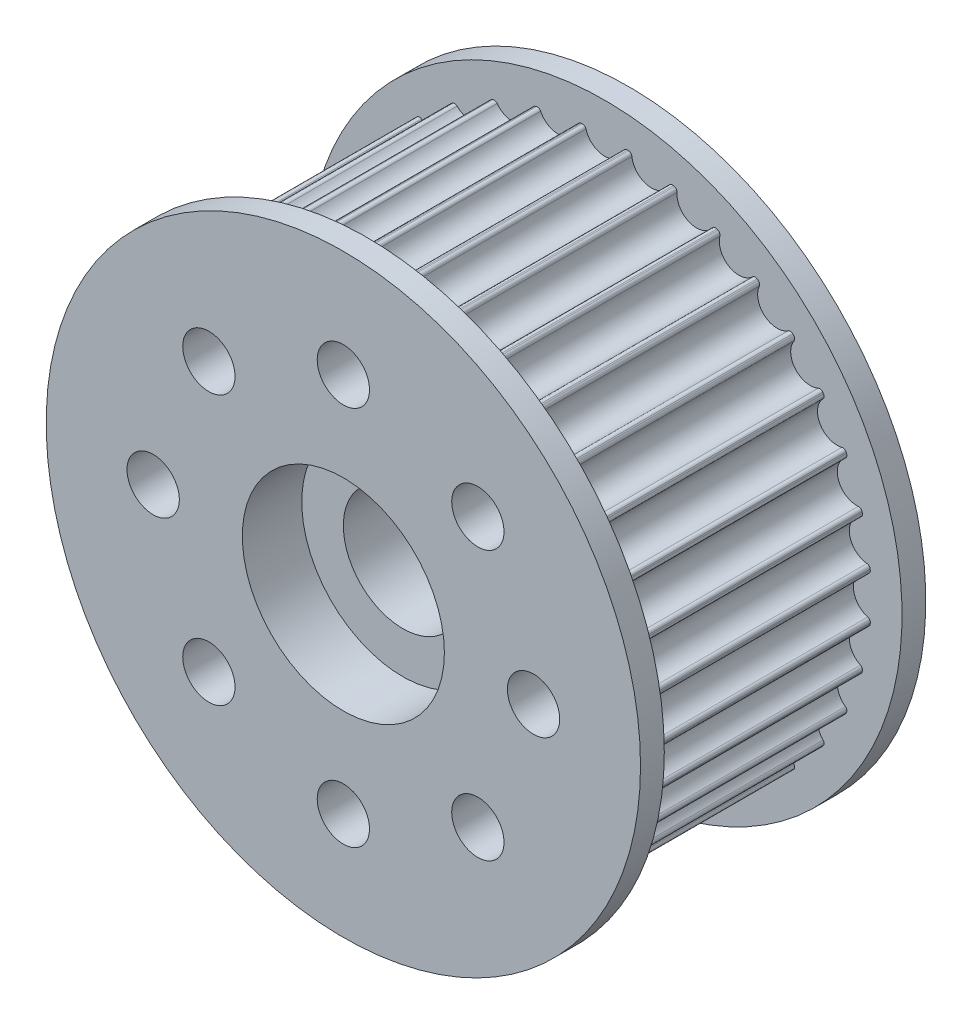
SolidWorks part; units mm, degrees
ref_plane "Front Plane" through (0, 0, 0) normal (0, 0, 1) x (1, 0, 0)
ref_plane "Top Plane" through (0, 0, 0) normal (0, 1, 0) x (1, 0, 0)
ref_plane "Right Plane" through (0, 0, 0) normal (1, 0, 0) x (0, 0, -1)
sketch "Sketch1" plane through (0, 0, 0) normal (0, 0, 1) x (1, 0, 0)
  line L0 (0, 0) -> (0, 11.46) construction
  line L1 (0, 0) -> (1.99, 11.2859) construction
  line L2 (0, 0) -> (1.8155, 10.2962)
  line L3 (0, 10.455) -> (0, 0)
  circle A0 centre (0, 0) radius 11.46 construction
  circle A1 centre (0, 0) radius 11.205 construction
  circle A2 centre (0, 0) radius 10.455 construction
  circle A5 centre (0, 11.28) radius 0.825 construction
  circle A6 centre (1.9588, 11.1086) radius 0.825 construction
  arc A7 (1.8155, 10.2962) -> (1.1347, 11.1474) centre (1.9588, 11.1086) cw
  arc A8 (1.1347, 11.1474) -> (0.8183, 11.1751) centre (0, 0) ccw
  arc A9 (0.8183, 11.1751) -> (0, 10.455) centre (0, 11.28) cw
  point P15 (0, 0)
  point P16 (0, 11.255)
  point P17 (0, 0)
  point P18 (0, 11.255)
  point P19 (0, 11.255)
  dimension "D1" = 22.92
  dimension "D2" = 22.41
  dimension "D4" = 0.75
  dimension "D5" = 1.65
  dimension "D3" = 10
extrude "Boss-Extrude1" add sketch "Sketch1" along normal mid plane 10
fillet "Fillet1" radius 0.15 2 edges at (1.1347, 11.1474, 0) (0.8183, 11.1751, 0)
pattern_circular "CirPattern1" count 36 every 10 about axis through (0, 0, 0) along (0, 0, 1) of "Boss-Extrude1", "Fillet1"
sketch "Sketch2" plane through (0, 0, 5) normal (0, 0, 1) x (1, 0, 0)
  circle A0 centre (0, 0) radius 12.5
  dimension "D1" = 25
extrude "Boss-Extrude2" add sketch "Sketch2" along normal blind 1
sketch "Sketch3" plane through (0, 0, -5) normal (0, 0, -1) x (-1, 0, 0)
  circle A0 centre (0, 0) radius 12.5 construction
  circle A1 centre (0, 0) radius 12.5
extrude "Boss-Extrude3" add sketch "Sketch3" along normal blind 1
hole_wizard "CBORE for M2 SHCS1" positions "Sketch5" profile "Sketch6" counterbore size "M2" standard "ANSI Metric" end condition through all
sketch "Sketch5" plane through (0, 0, -6) normal (0, 0, -1) x (-1, 0, 0)
  point P0 (0, 8)
  point P11 (5.6569, 5.6569)
  point P12 (8, 0)
  point P13 (5.6569, -5.6569)
  point P14 (0, -8)
  point P15 (-5.6569, -5.6569)
  point P16 (-8, 0)
  point P17 (-5.6569, 5.6569)
  dimension "D1" = 8
  dimension "D2" = 8
sketch "Sketch6" plane through (0, 8, -6) normal (1, 0, 0) x (0, 1, 0)
  line L0 (0, 0) -> (0, 12)
  line L1 (0, 12) -> (1.1, 12)
  line L3 (1.1, 12) -> (1.1, 2)
  line L4 (1.1, 2) -> (2.2, 2)
  line L5 (2.2, 2) -> (2.2, 0)
  line L7 (2.2, 0) -> (0, 0)
  line L11 (0, -6.35) -> (0, 107.95) construction
  dimension "Thru Hole Dia." = 2.2
  dimension "Thru Hole Depth" = 12
  dimension "C'Bore Dia." = 4.4
  dimension "C'Bore Depth" = 2
sketch "Sketch7" plane through (0, 0, 6) normal (0, 0, 1) x (1, 0, 0)
  circle A0 centre (0, 0) radius 4.25
  dimension "D1" = 8.5
extrude "Cut-Extrude1" cut sketch "Sketch7" against normal blind 2.5
sketch "Sketch8" plane through (0, 0, 6) normal (0, 0, 1) x (1, 0, 0)
  circle A0 centre (0, 0) radius 2.5
  dimension "D1" = 5
extrude "Cut-Extrude2" cut sketch "Sketch8" against normal blind 5
